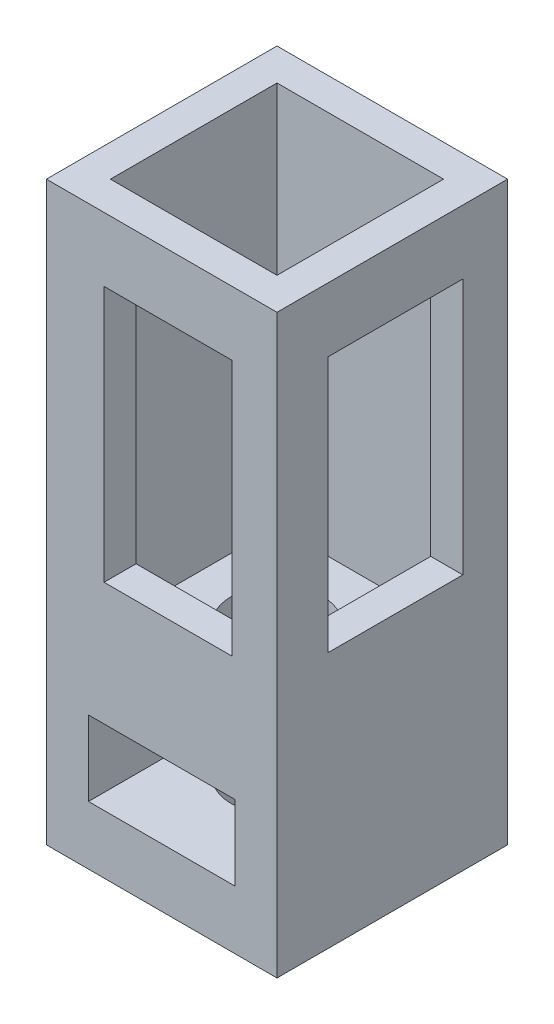
SolidWorks part; units mm, degrees
ref_plane "Front Plane" through (0, 0, 0) normal (0, 0, 1) x (1, 0, 0)
ref_plane "Top Plane" through (0, 0, 0) normal (0, 1, 0) x (1, 0, 0)
ref_plane "Right Plane" through (0, 0, 0) normal (1, 0, 0) x (0, 0, -1)
sketch "Sketch1" plane through (0, 0, 0) normal (0, 1, 0) x (1, 0, 0)
  line L1 (0, 0) -> (18, 0)
  line L2 (0, 0) -> (0, 18)
  line L3 (0, 18) -> (18, 18)
  line L4 (18, 0) -> (18, 18)
  dimension "D1" = 18
  dimension "D2" = 18
extrude "Boss-Extrude1" add sketch "Sketch1" along normal blind 35
sketch "Sketch5" plane through (0, 35, 0) normal (0, 1, 0) x (1, 0, 0)
  line L0 (-9.9, 0) -> (9.9, 0) construction
  line L1 (2.5, 15.5) -> (15.5, 15.5)
  line L2 (2.5, 15.5) -> (2.5, 2.5)
  line L3 (2.5, 2.5) -> (15.5, 2.5)
  line L4 (15.5, 15.5) -> (15.5, 2.5)
  line L5 (18, 18) -> (0, 18) construction
  line L6 (18, 0) -> (18, 18) construction
  dimension "D1" = 13
  dimension "D2" = 13
  dimension "D3" = 2.5
  dimension "D4" = 2.5
  dimension "D5" = 2.5
  dimension "D6" = 2.5
extrude "Cut-Extrude1" cut sketch "Sketch5" against normal blind 30
sketch "Sketch7" plane through (18, 0, 0) normal (1, 0, 0) x (0, 0, -1)
  line L0 (0, 35) -> (18, 35) construction
  line L1 (4, 30) -> (14.5, 30)
  line L2 (4, 30) -> (4, 10)
  line L3 (4, 10) -> (14.5, 10)
  line L4 (14.5, 30) -> (14.5, 10)
  line L5 (18, 35) -> (18, 0) construction
  line L6 (0, 9.9) -> (0, -9.9) construction
  dimension "D1" = 20
  dimension "D2" = 5
  dimension "D3" = 10.5
  dimension "D4" = 3.5
  dimension "D5" = 4
extrude "Cut-Extrude3" cut sketch "Sketch7" against normal up to next
sketch "Sketch8" plane through (0, 0, 0) normal (0, -1, 0) x (1, 0, 0)
  line L1 (0, 0) -> (18, 0)
  line L2 (0, 0) -> (0, -18)
  line L3 (0, -18) -> (18, -18)
  line L4 (18, 0) -> (18, -18)
extrude "Boss-Extrude2" add sketch "Sketch8" along normal blind 10
sketch "Sketch9" plane through (0, 0, 0) normal (0, 0, 1) x (1, 0, 0)
  line L0 (18, 35) -> (18, -10) construction
  line L1 (3.285, 0.425) -> (14.715, 0.425)
  line L2 (3.285, 0.425) -> (3.285, -5.425)
  line L3 (3.285, -5.425) -> (14.715, -5.425)
  line L4 (14.715, 0.425) -> (14.715, -5.425)
  line L5 (0, 35) -> (0, -10) construction
  line L6 (18, -10) -> (0, -10) construction
  line L7 (2.5, 5) -> (15.5, 5) construction
  dimension "D1" = 5.85
  dimension "D2" = 11.43
  dimension "D3" = 3.285
  dimension "D4" = 3.285
  dimension "D5" = 4.575
  dimension "D6" = 4.575
extrude "Cut-Extrude4" cut sketch "Sketch9" against normal through all
hole_wizard "1/4 Clearance Hole1" positions "Sketch11" profile "Sketch10" hole size "1/4" standard "ANSI Inch"
sketch "Sketch11" plane through (0, -10, 0) normal (0, -1, 0) x (-1, 0, 0)
  line L0 (-18, 0) -> (0, 0) construction
  line L1 (0, 18) -> (-18, 18) construction
  line L2 (-18, 18) -> (-18, 0) construction
  point P0 (-9, 9)
  dimension "D1" = 9
  dimension "D2" = 9
  dimension "D3" = 9
sketch "Sketch10" plane through (9, -10, -9) normal (1, 0, 0) x (0, 0, -1)
  line L0 (0, 0) -> (0, 17.1458)
  line L1 (0, 17.1458) -> (3.5712, 15)
  line L2 (3.5712, 15) -> (3.5712, 0)
  line L5 (3.5712, 0) -> (0, 0)
  line L10 (0, 17.1458) -> (-3.5712, 15) construction
  line L11 (0, -6.35) -> (0, 107.95) construction
  dimension "Hole Dia." = 7.1425
  dimension "Hole Depth" = 15
  dimension "Drill Angle" = 118
sketch "Sketch12" plane through (0, 0, 0) normal (0, 0, 1) x (1, 0, 0)
  line L0 (0, 35) -> (18, 35) construction
  line L1 (4.5, 30) -> (14.5, 30)
  line L2 (4.5, 30) -> (4.5, 10)
  line L3 (4.5, 10) -> (14.5, 10)
  line L4 (14.5, 30) -> (14.5, 10)
  line L5 (18, 35) -> (18, -10) construction
  dimension "D1" = 20
  dimension "D2" = 10
  dimension "D3" = 5
  dimension "D4" = 3.5
extrude "Cut-Extrude5" cut sketch "Sketch12" against normal up to next
